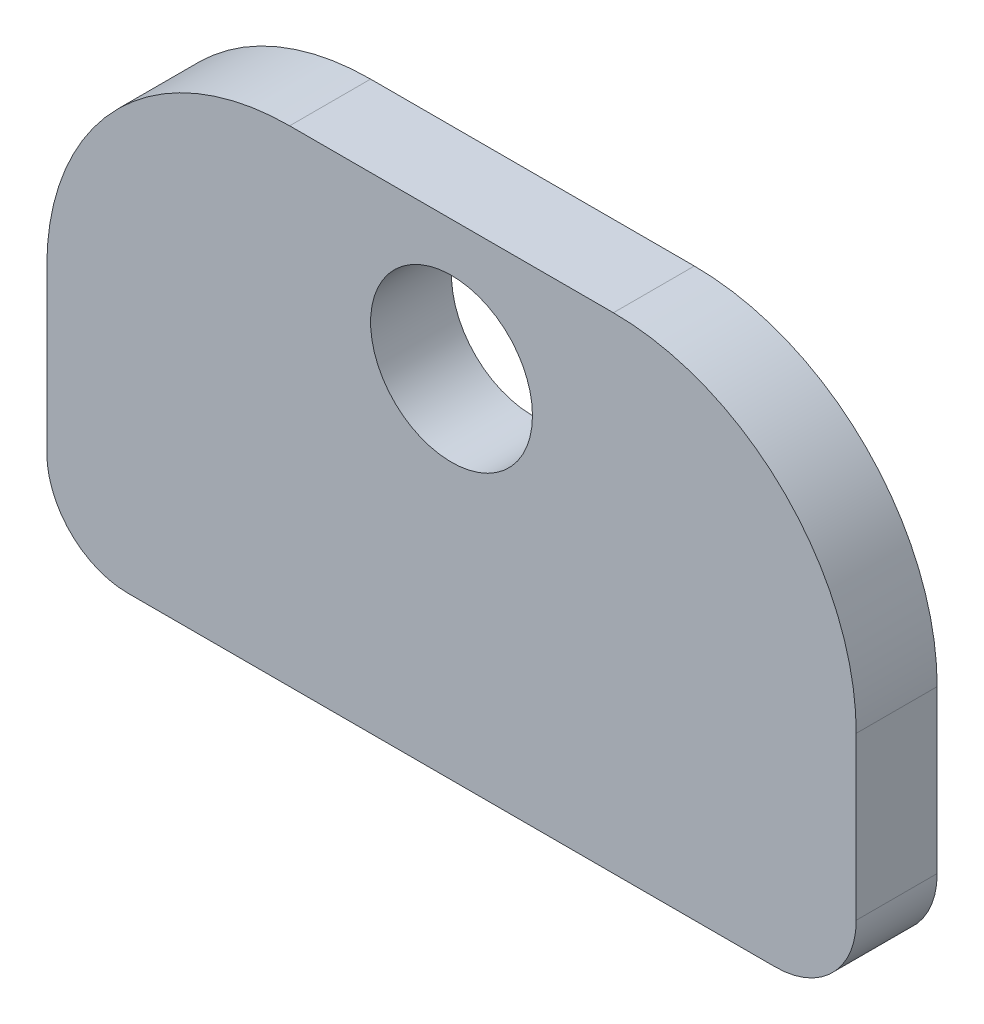
SolidWorks part; units mm, degrees
ref_plane "Płaszczyzna przednia" through (0, 0, 0) normal (0, 0, 1) x (1, 0, 0)
ref_plane "Płaszczyzna górna" through (0, 0, 0) normal (0, 1, 0) x (1, 0, 0)
ref_plane "Płaszczyzna prawa" through (0, 0, 0) normal (1, 0, 0) x (0, 0, -1)
sketch "Szkic1" plane through (0, 0, 0) normal (0, 0, 1) x (1, 0, 0)
  line L1 (-20, -15) -> (20, -15)
  line L2 (-25, -10) -> (-25, 0)
  line L3 (-10, 15) -> (10, 15)
  line L4 (25, -10) -> (25, 0)
  line L5 (-25, -15) -> (25, 15) construction
  line L6 (-25, 15) -> (25, -15) construction
  arc A0 (20, -15) -> (25, -10) centre (20, -10) ccw
  arc A1 (-25, -10) -> (-20, -15) centre (-20, -10) ccw
  arc A2 (10, 15) -> (25, 0) centre (10, 0) cw
  arc A3 (-25, 0) -> (-10, 15) centre (-10, 0) cw
  circle A4 centre (0, 7) radius 5
  point P0 (0, 0)
  dimension "D3" = 5
  dimension "D4" = 15
  dimension "D5" = 10
  dimension "D1" = 50
  dimension "D2" = 30
  dimension "D6" = 7
  dimension "D7" = 25
extrude "Dodanie-wyciągnięcie1" add sketch "Szkic1" along normal blind 5
